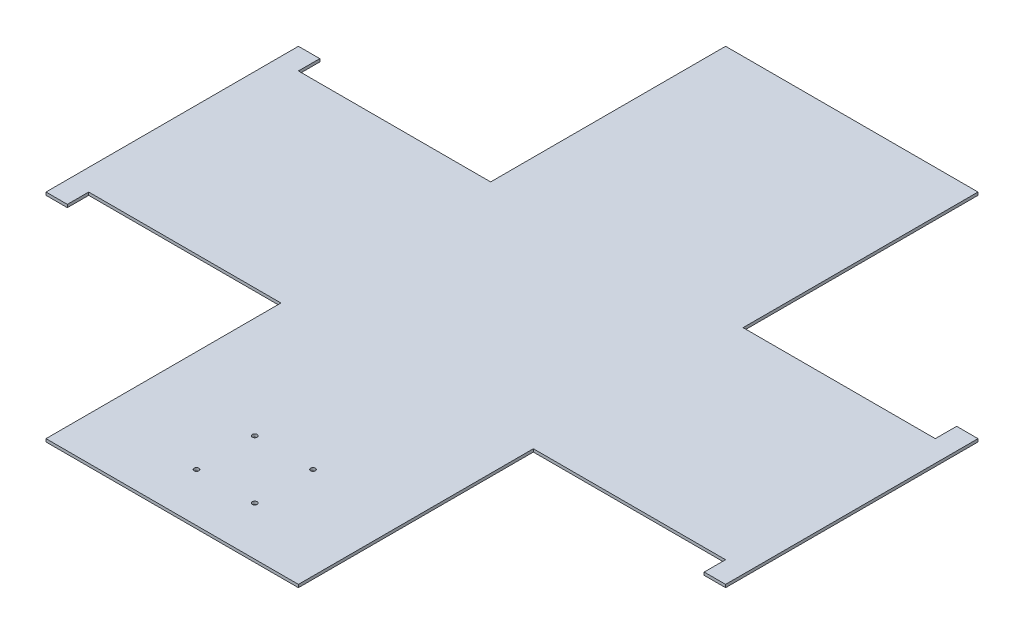
SolidWorks part; units mm, degrees
ref_plane "Front Plane" through (0, 0, 0) normal (0, 0, 1) x (1, 0, 0)
ref_plane "Top Plane" through (0, 0, 0) normal (0, 1, 0) x (1, 0, 0)
ref_plane "Right Plane" through (0, 0, 0) normal (1, 0, 0) x (0, 0, -1)
sketch "Sketch1" plane through (0, 0, 0) normal (0, 1, 0) x (1, 0, 0)
  line L0 (-350, -130) -> (-328, -130)
  line L1 (-130, -350) -> (130, -350)
  line L2 (-350, -130) -> (-350, 130)
  line L3 (-130, 350) -> (130, 350)
  line L4 (350, -130) -> (350, 130)
  line L7 (-350, 350) -> (-130, 350) construction
  line L8 (-350, 350) -> (-350, 130) construction
  line L9 (-350, 130) -> (-328, 130)
  line L10 (-130, 350) -> (-130, 130)
  line L11 (-350, 350) -> (-130, 130) construction
  line L12 (-350, 130) -> (-130, 350) construction
  line L13 (-350, -130) -> (-350, -350) construction
  line L14 (-350, -350) -> (-130, -350) construction
  line L15 (-130, -130) -> (-130, -350)
  line L16 (-350, -130) -> (-130, -350) construction
  line L17 (-350, -350) -> (-130, -130) construction
  line L18 (130, 350) -> (350, 350) construction
  line L19 (130, 350) -> (130, 130)
  line L20 (328, 130) -> (350, 130)
  line L21 (350, 350) -> (350, 130) construction
  line L22 (130, 350) -> (350, 130) construction
  line L23 (130, 130) -> (350, 350) construction
  line L24 (328, -130) -> (350, -130)
  line L25 (130, -130) -> (130, -350)
  line L26 (130, -350) -> (350, -350) construction
  line L27 (350, -130) -> (350, -350) construction
  line L28 (130, -130) -> (350, -350) construction
  line L29 (130, -350) -> (350, -130) construction
  line L30 (-328, -108) -> (-130, -108)
  line L31 (-328, 130) -> (-130, 130) construction
  line L32 (-328, 130) -> (-328, 108)
  line L33 (-328, 108) -> (-130, 108)
  line L34 (-130, 130) -> (-130, 108)
  line L35 (-328, 130) -> (-130, 108) construction
  line L36 (-328, 108) -> (-130, 130) construction
  line L37 (-328, -108) -> (-328, -130)
  line L38 (-328, -130) -> (-130, -130) construction
  line L39 (-130, -108) -> (-130, -130)
  line L40 (-328, -108) -> (-130, -130) construction
  line L41 (-328, -130) -> (-130, -108) construction
  line L42 (130, 130) -> (328, 130) construction
  line L43 (130, 130) -> (130, 108)
  line L44 (130, 108) -> (328, 108)
  line L45 (328, 130) -> (328, 108)
  line L46 (130, 130) -> (328, 108) construction
  line L47 (130, 108) -> (328, 130) construction
  line L48 (130, -108) -> (328, -108)
  line L49 (130, -108) -> (130, -130)
  line L50 (130, -130) -> (328, -130) construction
  line L51 (328, -108) -> (328, -130)
  line L52 (130, -108) -> (328, -130) construction
  line L53 (130, -130) -> (328, -108) construction
  line L54 (-130, 350) -> (130, -350) construction
  point P0 (0, 0)
  point P1 (0, 0)
  point P10 (-240, 240)
  point P15 (-240, -240)
  point P20 (240, 240)
  point P25 (240, -240)
  point P30 (-229, 119)
  point P35 (-229, -119)
  point P40 (229, 119)
  point P45 (229, -119)
  dimension "D3" = 220
  dimension "D4" = 220
  dimension "D5" = 220
  dimension "D6" = 220
  dimension "D7" = 220
  dimension "D8" = 220
  dimension "D9" = 220
  dimension "D10" = 220
  dimension "D11" = 22
  dimension "D12" = 198
  dimension "D13" = 22
  dimension "D14" = 198
  dimension "D15" = 22
  dimension "D16" = 198
  dimension "D17" = 22
  dimension "D18" = 198
extrude "Base" add sketch "Sketch1" along normal blind 3
sketch "Sketch2" plane through (0, 0, 0) normal (0, -1, 0) x (1, 0, 0)
  line L0 (-25, 300) -> (35, 300) construction
  line L1 (35, 300) -> (35, 240) construction
  line L2 (35, 240) -> (-25, 240) construction
  line L3 (-25, 240) -> (-25, 300) construction
  line L4 (-130, 350) -> (130, 350) construction
  line L8 (-350, -130) -> (-350, 130) construction
  line L9 (5, 300) -> (5, 240) construction
  line L10 (-25, 270) -> (35, 270) construction
  circle A0 centre (-25, 300) radius 2.5
  circle A1 centre (35, 300) radius 2.5
  circle A2 centre (-25, 240) radius 2.5
  circle A3 centre (35, 240) radius 2.5
  dimension "D1" = 5
  dimension "D2" = 60
  dimension "D3" = 60
  dimension "D4" = 325
  dimension "D5" = 50
extrude "Cut-Extrude2" cut sketch "Sketch2" against normal through all
ref_plane "PPM_RPlane" through (5, 0, 0) normal (1, 0, 0) x (0, 0, -1)
ref_plane "PMM_FPlane" through (0, 0, 270) normal (0, 0, 1) x (1, 0, 0)
